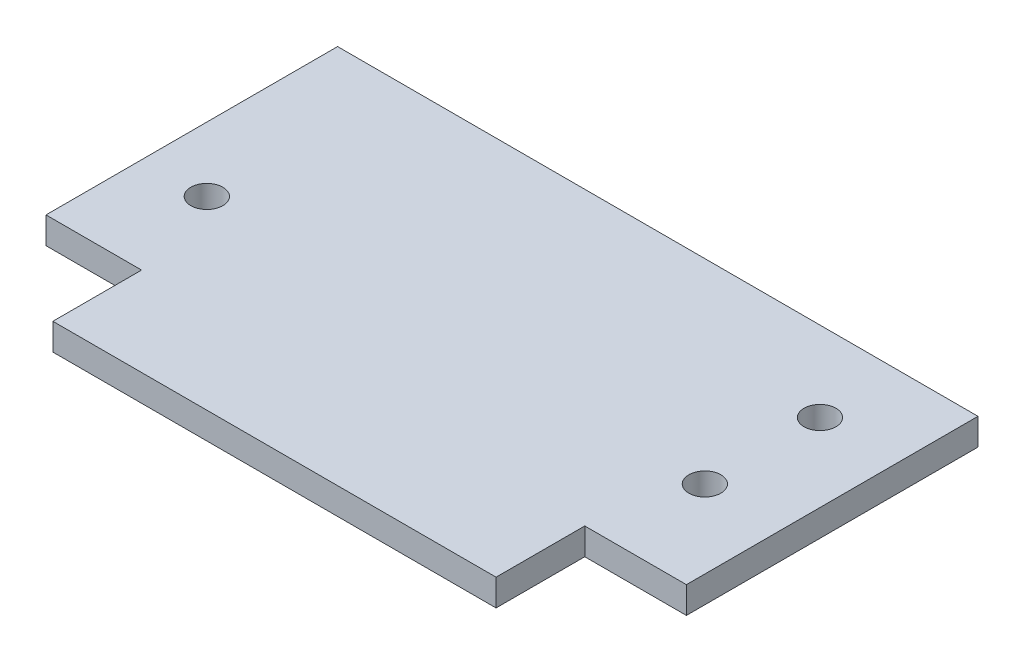
SolidWorks part; units mm, degrees
ref_plane "Front" through (0, 0, 0) normal (0, 0, 1) x (1, 0, 0)
ref_plane "Top" through (0, 0, 0) normal (0, 1, 0) x (1, 0, 0)
ref_plane "Right" through (0, 0, 0) normal (1, 0, 0) x (0, 0, -1)
sketch "Sketch1" plane through (0, 0, 0) normal (0, 1, 0) x (1, 0, 0)
  line L1 (0, 0) -> (72, 0)
  line L2 (0, 0) -> (0, 42.755)
  line L3 (0, 42.755) -> (72, 42.755)
  line L4 (72, 0) -> (72, 42.755)
  dimension "D1" = 72
  dimension "D2" = 42.755
extrude "Boss-Extrude1" add sketch "Sketch1" along normal blind 3
sketch "Sketch2" plane through (0, 3, 0) normal (0, 1, 0) x (1, 0, 0)
  line L0 (72, 42.755) -> (0, 42.755) construction
  circle A0 centre (7.2441, 20.8097) radius 1.8
  circle A1 centre (63.2344, 20.8097) radius 1.8
  circle A2 centre (63.2344, 33.755) radius 1.8
  dimension "D1" = 9
extrude "Cut-Extrude1" cut sketch "Sketch2" against normal blind 3
sketch "Sketch3" plane through (0, 3, 0) normal (0, 1, 0) x (1, 0, 0)
  line L0 (0, 0) -> (72, 0) construction
  line L1 (10.7435, 0) -> (0, 0)
  line L2 (10.7435, 0) -> (10.7435, 9.972)
  line L3 (10.7435, 9.972) -> (0, 9.972)
  line L4 (0, 0) -> (0, 9.972)
  line L5 (0, 42.755) -> (0, 0) construction
  line L6 (72, 0) -> (72, 42.755) construction
  line L7 (60.5719, 0) -> (80.9597, 0)
  line L8 (60.5719, 0) -> (60.5719, 2.175)
  line L9 (60.5719, 2.175) -> (80.9597, 2.175)
  line L10 (80.9597, 0) -> (80.9597, 2.175)
  line L12 (60.5719, 2.175) -> (60.5719, 9.972)
  line L13 (60.5719, 9.972) -> (72, 9.972)
  line L14 (72, 2.175) -> (72, 9.972)
  line M4 (0, 42.755) -> (0, 0)
  line M5 (0, 0) -> (72, 0)
  line M6 (72, 0) -> (72, 42.755)
extrude "Cut-Extrude2" cut sketch "Sketch3" against normal blind 53 contours L2 L3 M4 M5 | L13 L12 L9 M6 | L9 L8 M5 M6
